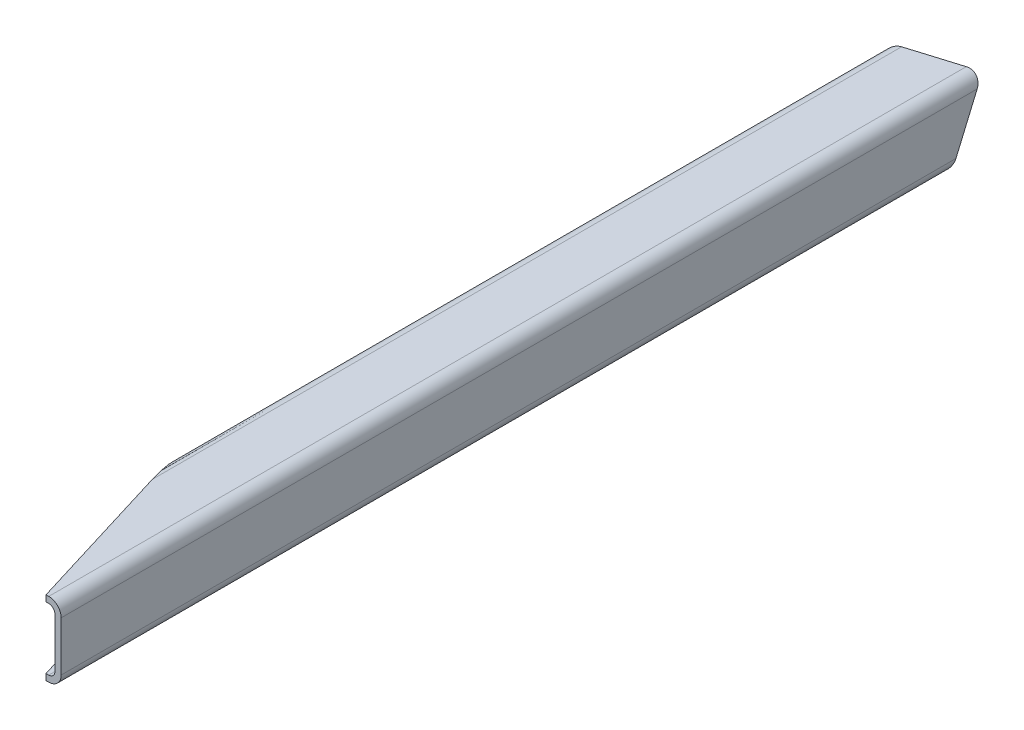
SolidWorks part; units mm, degrees
material "ASTM A36 Steel"
ref_plane "Front Plane" through (0, 0, 0) normal (0, 0, 1) x (1, 0, 0)
ref_plane "Top Plane" through (0, 0, 0) normal (0, 1, 0) x (1, 0, 0)
ref_plane "Right Plane" through (0, 0, 0) normal (1, 0, 0) x (0, 0, -1)
sketch "Sketch1" plane through (0, 0, 0) normal (0, 0, 1) x (1, 0, 0)
  line L0 (-25.4, 31.75) -> (25.4, 31.75)
  line L1 (-25.4, -38.1) -> (25.4, -38.1)
  line L2 (-38.1, -25.4) -> (-38.1, 25.4)
  line L3 (-25.4, 38.1) -> (25.4, 38.1)
  line L4 (38.1, -25.4) -> (38.1, 25.4)
  line L5 (-38.1, -38.1) -> (38.1, 38.1) construction
  line L6 (-38.1, 38.1) -> (38.1, -38.1) construction
  line L7 (31.75, -25.4) -> (31.75, 25.4)
  line L8 (-25.4, -31.75) -> (25.4, -31.75)
  line L9 (-31.75, -25.4) -> (-31.75, 25.4)
  arc A0 (25.4, -38.1) -> (38.1, -25.4) centre (25.4, -25.4) ccw
  arc A1 (-38.1, 25.4) -> (-25.4, 38.1) centre (-25.4, 25.4) cw
  arc A2 (-25.4, -38.1) -> (-38.1, -25.4) centre (-25.4, -25.4) cw
  arc A3 (25.4, 38.1) -> (38.1, 25.4) centre (25.4, 25.4) cw
  arc A4 (25.4, 31.75) -> (31.75, 25.4) centre (25.4, 25.4) cw
  arc A5 (25.4, -31.75) -> (31.75, -25.4) centre (25.4, -25.4) ccw
  arc A6 (-25.4, -31.75) -> (-31.75, -25.4) centre (-25.4, -25.4) cw
  arc A7 (-31.75, 25.4) -> (-25.4, 31.75) centre (-25.4, 25.4) cw
  point P0 (0, 0)
  dimension "D3" = 12.7
  dimension "D1" = 76.2
  dimension "D2" = 76.2
  dimension "D4" = 6.35
extrude "Boss-Extrude1" add sketch "Sketch1" along normal mid plane 1168.4
ref_plane "Plane1" through (-145.7731, 0, 50.1937) normal (-0.9455, 0, 0.3256) x (0, 1, 0)
sketch "Sketch2" plane through (0, 0, 0) normal (0, 1, 0) x (1, 0, 0)
  line L0 (-38.1, -584.2) -> (38.1, -584.2)
  line L1 (-159.4177, -10.567) -> (-132.1286, -89.8204) construction
  line L2 (38.1, -584.2) -> (38.1, 584.2) construction
  line L3 (38.1, -584.2) -> (-38.1, -334.961)
  line L4 (-38.1, -584.2) -> (-38.1, 584.2) construction
  line L5 (-38.1, -334.961) -> (-38.1, -584.2)
  dimension "D1" = 73
extrude "Cut-Extrude1" cut sketch "Sketch2" against normal through all and the other way blind 1168.4
sketch "Sketch3" plane through (0, 0, 0) normal (1, 0, 0) x (0, 0, -1)
  line L0 (529.2248, 234.9129) -> (393.7, -38.1)
  line L1 (393.7, -38.1) -> (621.2108, -151.0373)
  line L2 (621.2108, -151.0373) -> (756.7356, 121.9756)
  line L3 (756.7356, 121.9756) -> (529.2248, 234.9129)
  line L4 (-542.6602, -38.1) -> (584.2, -38.1) construction
  line L5 (584.2, 25.4) -> (584.2, -25.4) construction
  dimension "D1" = 254
  dimension "D2" = 304.8
  dimension "D3" = 63.6
  dimension "D4" = 190.5
extrude "Cut-Extrude2" cut sketch "Sketch3" against normal through all and the other way through all
sketch "Sketch4" plane through (0, 38.1, 0) normal (0, 1, 0) x (1, 0, 0)
  line L0 (22.5689, -533.4) -> (38.1, -533.4)
  line L1 (25.4, -542.6602) -> (-25.4, -376.5009) construction
  line L2 (38.1, -584.2) -> (38.1, 425.2217) construction
  line L3 (38.1, -533.4) -> (38.1, -584.2)
  line L4 (-150.3213, -36.9848) -> (-141.2249, -63.4026) construction
  line L5 (38.1, -584.2) -> (22.5689, -533.4)
  dimension "D1" = 50.8
extrude "Cut-Extrude3" cut sketch "Sketch4" against normal through all
ref_plane "Plane2" through (-91.7766, -128.4802, -300.1877) normal (0.2706, 0.3788, 0.885) x (0.9627, -0.1065, -0.2488)
other "SurfaceCut1"
equation "\"PRIMER_USAGE\"= ( \"SW-SurfaceArea\" / 144 ) / 135"
equation "\"WET_PAINT_USAGE\"= ( \"SW-SurfaceArea\" / 144 ) / 125"
equation "\"POWDERCOAT_USAGE\"= ( \"SW-SurfaceArea\" / 144 ) / 29.79"
equation "\"DECKOVER_USAGE\"= ( \"SW-SurfaceArea\" / 144 ) / 75"
equation "\"SW_NON-SKID\"= ( \"SW-SurfaceArea\" / 144 ) / 165"
equation "\"TYPE_1_ANODIZATING\"= ( \"SW-SurfaceArea\" * 0.0001 )"
equation "\"TYPE_2_ANODIZING\"= ( \"SW-SurfaceArea\" * 0.0005 )"
equation "\"TYPE_3_ANODIZING-HARDCOAT\"= ( \"SW-SurfaceArea\" * 0.003 )"
